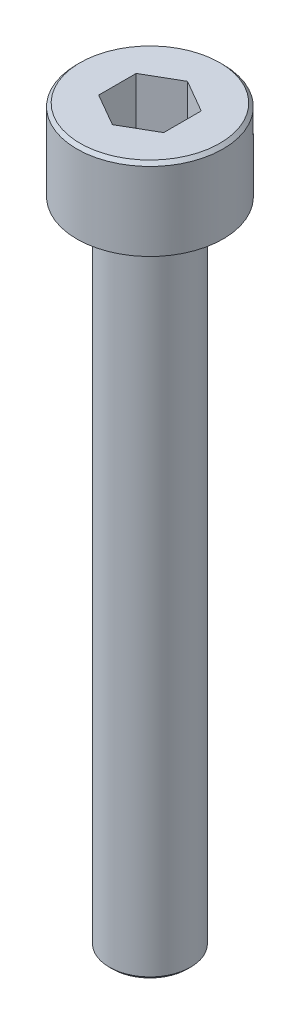
SolidWorks part; units mm, degrees
material "AISI 316, barra ricotta (SS)"
ref_plane "Piano frontale" through (0, 0, 0) normal (0, 0, 1) x (1, 0, 0)
ref_plane "Piano superiore" through (0, 0, 0) normal (0, 1, 0) x (1, 0, 0)
ref_plane "Piano destro" through (0, 0, 0) normal (1, 0, 0) x (0, 0, -1)
sketch "Schizzo1" plane through (0, 0, 0) normal (0, 0, 1) x (1, 0, 0)
  line L0 (0, 0) -> (0, 2.5)
  line L1 (0, 2.5) -> (2.25, 2.5)
  line L2 (2.25, 2.5) -> (2.25, 0)
  line L3 (2.25, 0) -> (1.25, 0)
  line L4 (1.25, 0) -> (1.25, -20)
  line L5 (1.25, -20) -> (0, -20)
  line L6 (0, -20) -> (0, 0)
  line L7 (0, 28.3885) -> (0, -27.6749) construction
  dimension "D1" = 2.5
  dimension "D2" = 2.5
  dimension "D3" = 4.5
  dimension "D4" = 20
revolve "Rivoluzione1" add sketch "Schizzo1" angle 360 about L7
chamfer "Smusso1" distance 0.1 angle 45 2 edges at (0, 2.5, 2.25) (0, -20, 1.25)
sketch "Schizzo2" plane through (0, 2.5, 0) normal (0, 1, 0) x (1, 0, 0)
  line L1 (0, 1.1547) -> (-1, 0.5774)
  line L2 (-1, 0.5774) -> (-1, -0.5774)
  line L3 (-1, -0.5774) -> (0, -1.1547)
  line L4 (0, -1.1547) -> (1, -0.5774)
  line L5 (1, -0.5774) -> (1, 0.5774)
  line L6 (1, 0.5774) -> (0, 1.1547)
  circle A0 centre (0, 0) radius 1 construction
  dimension "D1" = 2
extrude "Taglio-Estrusione1" cut sketch "Schizzo2" against normal blind 2
